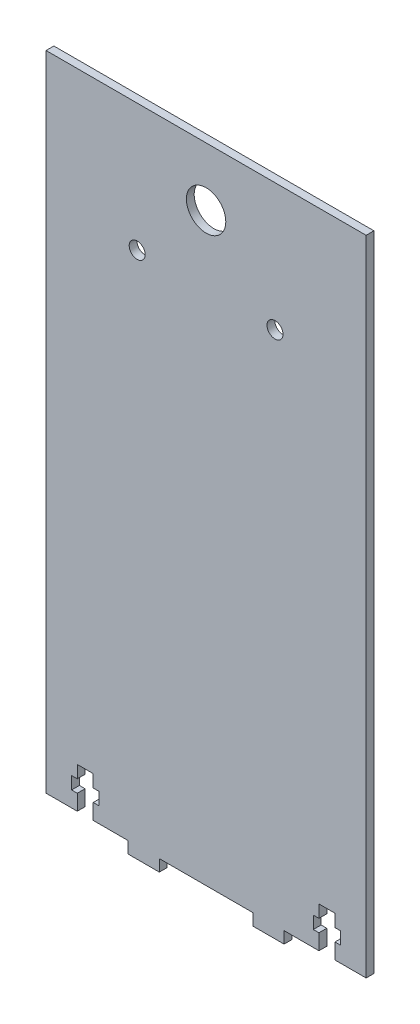
SolidWorks part; units mm, degrees
ref_plane "前视基准面" through (0, 0, 0) normal (0, 0, 1) x (1, 0, 0)
ref_plane "上视基准面" through (0, 0, 0) normal (0, 1, 0) x (1, 0, 0)
ref_plane "右视基准面" through (0, 0, 0) normal (1, 0, 0) x (0, 0, -1)
sketch "草图1" plane through (0, 0, 0) normal (0, 0, 1) x (1, 0, 0)
  line L0 (-30.7912, 3.1303) -> (31.2088, 3.1303) construction
  line L1 (-30.7912, 3.1303) -> (-30.7912, 5.1553) construction
  line L2 (-28.7412, 3.1303) -> (-28.7412, 7.1303)
  line L3 (-28.7412, 7.1303) -> (-27.2912, 7.1303)
  line L4 (-27.2912, 7.1303) -> (-27.2912, 10.3303)
  line L5 (-27.2912, 10.3303) -> (-28.7412, 10.3303)
  line L6 (-28.7412, 10.3303) -> (-28.7412, 13.5303)
  line L7 (-28.7412, 13.5303) -> (-32.8412, 13.5303)
  line L8 (-34.2912, 7.1303) -> (-34.2912, 10.3303)
  line L9 (-32.8412, 10.3303) -> (-32.8412, 13.5303)
  line L10 (-32.8412, 3.1303) -> (-32.8412, 7.1303)
  line L11 (-32.8412, 7.1303) -> (-34.2912, 7.1303)
  line L12 (-34.2912, 10.3303) -> (-32.8412, 10.3303)
  line L13 (-32.8412, 3.1303) -> (-40.8412, 3.1303)
  line L14 (-40.8412, 3.1303) -> (-40.8412, 168.1303)
  line L15 (-19.7912, 3.1303) -> (-19.7912, 0.1303)
  line L16 (-19.7912, 0.1303) -> (-11.7912, 0.1303)
  line L17 (-11.7912, 0.1303) -> (-11.7912, 3.1303)
  line L18 (-15.7912, 0.1303) -> (-15.7912, 3.1303) construction
  line L19 (-28.7412, 3.1303) -> (-19.7912, 3.1303)
  line L20 (0.2088, 3.1303) -> (0.2088, -7.8241) construction
  line L21 (-11.7912, 3.1303) -> (12.2088, 3.1303)
  line L22 (16.2088, 0.1303) -> (16.2088, 3.1303) construction
  line L23 (31.2088, 3.1303) -> (31.2088, 5.1553) construction
  line L24 (29.1588, 3.1303) -> (20.2088, 3.1303)
  line L25 (12.2088, 0.1303) -> (12.2088, 3.1303)
  line L26 (20.2088, 0.1303) -> (12.2088, 0.1303)
  line L27 (20.2088, 3.1303) -> (20.2088, 0.1303)
  line L28 (41.2588, 3.1303) -> (41.2588, 168.1303)
  line L29 (33.2588, 3.1303) -> (41.2588, 3.1303)
  line L30 (34.7088, 10.3303) -> (33.2588, 10.3303)
  line L31 (33.2588, 7.1303) -> (34.7088, 7.1303)
  line L32 (33.2588, 3.1303) -> (33.2588, 7.1303)
  line L33 (33.2588, 10.3303) -> (33.2588, 13.5303)
  line L34 (34.7088, 7.1303) -> (34.7088, 10.3303)
  line L35 (29.1588, 13.5303) -> (33.2588, 13.5303)
  line L36 (29.1588, 10.3303) -> (29.1588, 13.5303)
  line L37 (27.7088, 10.3303) -> (29.1588, 10.3303)
  line L38 (27.7088, 7.1303) -> (27.7088, 10.3303)
  line L39 (29.1588, 7.1303) -> (27.7088, 7.1303)
  line L40 (29.1588, 3.1303) -> (29.1588, 7.1303)
  line L41 (-40.8412, 168.1303) -> (41.2588, 168.1303)
  line L42 (0.2088, 3.1303) -> (0.2088, 153.1303) construction
  line L43 (0.2088, 153.1303) -> (57.1498, 96.1893) construction
  circle A0 centre (0.2088, 153.1303) radius 5.05
  circle A1 centre (0.2088, 153.1303) radius 25 construction
  circle A2 centre (17.8865, 135.4526) radius 2.05
  circle A3 centre (-17.4689, 135.4526) radius 2.05
  point P16 (-30.7912, 13.5303)
  point P47 (31.2088, 13.5303)
  dimension "D10" = 10.1
  dimension "D13" = 50
  dimension "D14" = 4.1
  dimension "D1" = 62
  dimension "D2" = 2.05
  dimension "D3" = 3.2
  dimension "D4" = 4
  dimension "D5" = 3.5
  dimension "D6" = 8
  dimension "D7" = 3
  dimension "D8" = 15
  dimension "D9" = 8
  dimension "D11" = 150
  dimension "D12" = 45
  dimension "D15" = 15
extrude "凸台-拉伸1" add sketch "草图1" along normal blind 2
sketch "草图2" plane through (0, 3.1303, 0) normal (0, -1, 0) x (1, 0, 0)
  line L0 (29.1588, 1) -> (33.2588, 1) construction
  line L1 (29.1588, 2) -> (29.1588, 0) construction
  line L2 (33.2588, 2) -> (33.2588, 0) construction
  circle A0 centre (31.2088, 1) radius 2.05
